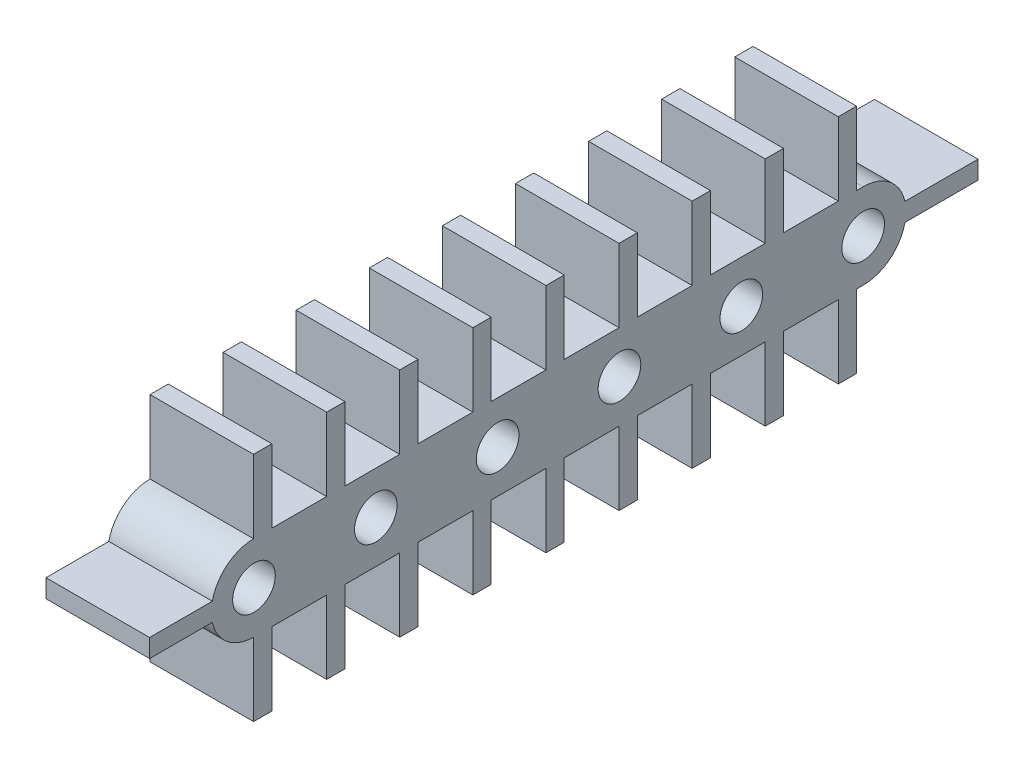
SolidWorks part; units mm, degrees
ref_plane "Front Plane" through (0, 0, 0) normal (0, 0, 1) x (1, 0, 0)
ref_plane "Top Plane" through (0, 0, 0) normal (0, 1, 0) x (1, 0, 0)
ref_plane "Right Plane" through (0, 0, 0) normal (1, 0, 0) x (0, 0, -1)
sketch "Sketch1" plane through (0, 0, 0) normal (1, 0, 0) x (0, 0, -1)
  line L0 (-265.082, 35) -> (-265.082, 95) construction
  line L1 (-250.082, 35) -> (-205.082, 35)
  line L3 (-250.082, -35) -> (-205.082, -35)
  line L5 (-185.082, 35) -> (-145.082, 35)
  line L7 (-265.082, 95) -> (-250.082, 95) construction
  line L8 (-250.082, 95) -> (-250.082, 35) construction
  line L9 (-265.082, 35) -> (-265.082, 95)
  line L10 (-265.082, 95) -> (-250.082, 95)
  line L11 (-250.082, 95) -> (-250.082, 35)
  line L23 (-264.7097, 0) -> (-265.3749, -51.003) construction
  line L27 (-205.082, 35) -> (-205.082, 95)
  line L28 (-205.082, 95) -> (-190.082, 95)
  line L29 (-190.082, 95) -> (-190.082, 35)
  line L30 (-205.082, 35) -> (-205.082, 95) construction
  line L31 (-205.082, 95) -> (-190.082, 95) construction
  line L32 (-190.082, 95) -> (-190.082, 35) construction
  line L33 (-145.082, 35) -> (-145.082, 95)
  line L34 (-145.082, 95) -> (-130.082, 95)
  line L35 (-130.082, 95) -> (-130.082, 35)
  line L36 (-145.082, 35) -> (-145.082, 95) construction
  line L37 (-145.082, 95) -> (-130.082, 95) construction
  line L38 (-130.082, 95) -> (-130.082, 35) construction
  line L39 (-85.082, 35) -> (-85.082, 95)
  line L40 (-85.082, 95) -> (-70.082, 95)
  line L41 (-70.082, 95) -> (-70.082, 35)
  line L42 (-85.082, 35) -> (-85.082, 95) construction
  line L43 (-85.082, 95) -> (-70.082, 95) construction
  line L44 (-70.082, 95) -> (-70.082, 35) construction
  line L45 (-25.082, 35) -> (-25.082, 95)
  line L46 (-25.082, 95) -> (-10.082, 95)
  line L47 (-10.082, 95) -> (-10.082, 35)
  line L48 (-25.082, 35) -> (-25.082, 95) construction
  line L49 (-25.082, 95) -> (-10.082, 95) construction
  line L50 (-10.082, 95) -> (-10.082, 35) construction
  line L51 (34.918, 35) -> (34.918, 95)
  line L52 (34.918, 95) -> (49.918, 95)
  line L53 (49.918, 95) -> (49.918, 35)
  line L54 (34.918, 35) -> (34.918, 95) construction
  line L55 (34.918, 95) -> (49.918, 95) construction
  line L56 (49.918, 95) -> (49.918, 35) construction
  line L57 (94.918, 35) -> (94.918, 95)
  line L58 (94.918, 95) -> (109.918, 95)
  line L59 (109.918, 95) -> (109.918, 35)
  line L60 (94.918, 35) -> (94.918, 95) construction
  line L61 (94.918, 95) -> (109.918, 95) construction
  line L62 (109.918, 95) -> (109.918, 35) construction
  line L63 (154.918, 35) -> (154.918, 95)
  line L64 (154.918, 95) -> (169.918, 95)
  line L65 (169.918, 95) -> (169.918, 35)
  line L66 (154.918, 35) -> (154.918, 95) construction
  line L67 (154.918, 95) -> (169.918, 95) construction
  line L68 (169.918, 95) -> (169.918, 35) construction
  line L69 (214.918, 35) -> (214.918, 95)
  line L70 (214.918, 95) -> (229.918, 95)
  line L71 (229.918, 95) -> (229.918, 35)
  line L72 (214.918, 35) -> (214.918, 95) construction
  line L73 (214.918, 95) -> (229.918, 95) construction
  line L74 (229.918, 95) -> (229.918, 35) construction
  line L75 (-190.082, 35) -> (-185.082, 35)
  line L76 (-130.082, 35) -> (-85.082, 35)
  line L77 (-70.082, 35) -> (-25.082, 35)
  line L78 (-10.082, 35) -> (34.918, 35)
  line L79 (49.918, 35) -> (94.918, 35)
  line L80 (109.918, 35) -> (154.918, 35)
  line L81 (169.918, 35) -> (214.918, 35)
  line L82 (229.918, 35) -> (235.3745, 35)
  line L83 (-264.7097, 0) -> (235.3745, 0) construction
  line L84 (229.918, -95) -> (229.918, -35) construction
  line L85 (214.918, -95) -> (229.918, -95) construction
  line L86 (214.918, -35) -> (214.918, -95) construction
  line L87 (169.918, -95) -> (169.918, -35) construction
  line L88 (154.918, -95) -> (169.918, -95) construction
  line L89 (154.918, -35) -> (154.918, -95) construction
  line L90 (109.918, -95) -> (109.918, -35) construction
  line L91 (94.918, -95) -> (109.918, -95) construction
  line L92 (94.918, -35) -> (94.918, -95) construction
  line L93 (49.918, -95) -> (49.918, -35) construction
  line L94 (34.918, -95) -> (49.918, -95) construction
  line L95 (34.918, -35) -> (34.918, -95) construction
  line L96 (-10.082, -95) -> (-10.082, -35) construction
  line L97 (-25.082, -95) -> (-10.082, -95) construction
  line L98 (-25.082, -35) -> (-25.082, -95) construction
  line L99 (-70.082, -95) -> (-70.082, -35) construction
  line L100 (-85.082, -95) -> (-70.082, -95) construction
  line L101 (-85.082, -35) -> (-85.082, -95) construction
  line L102 (-130.082, -95) -> (-130.082, -35) construction
  line L103 (-145.082, -95) -> (-130.082, -95) construction
  line L104 (-145.082, -35) -> (-145.082, -95) construction
  line L105 (-190.082, -95) -> (-190.082, -35) construction
  line L106 (-205.082, -95) -> (-190.082, -95) construction
  line L107 (-205.082, -35) -> (-205.082, -95) construction
  line L108 (-250.082, -95) -> (-250.082, -35) construction
  line L109 (-265.082, -95) -> (-250.082, -95) construction
  line L110 (-265.082, -35) -> (-265.082, -95) construction
  line L111 (229.918, -95) -> (229.918, -35)
  line L112 (214.918, -95) -> (229.918, -95)
  line L113 (214.918, -35) -> (214.918, -95)
  line L114 (169.918, -95) -> (169.918, -35)
  line L115 (154.918, -95) -> (169.918, -95)
  line L116 (154.918, -35) -> (154.918, -95)
  line L117 (109.918, -95) -> (109.918, -35)
  line L118 (94.918, -95) -> (109.918, -95)
  line L119 (94.918, -35) -> (94.918, -95)
  line L120 (49.918, -95) -> (49.918, -35)
  line L121 (34.918, -95) -> (49.918, -95)
  line L122 (34.918, -35) -> (34.918, -95)
  line L123 (-10.082, -95) -> (-10.082, -35)
  line L124 (-25.082, -95) -> (-10.082, -95)
  line L125 (-25.082, -35) -> (-25.082, -95)
  line L126 (-70.082, -95) -> (-70.082, -35)
  line L127 (-85.082, -95) -> (-70.082, -95)
  line L128 (-85.082, -35) -> (-85.082, -95)
  line L129 (-130.082, -95) -> (-130.082, -35)
  line L130 (-145.082, -95) -> (-130.082, -95)
  line L131 (-145.082, -35) -> (-145.082, -95)
  line L132 (-190.082, -95) -> (-190.082, -35)
  line L133 (-205.082, -95) -> (-190.082, -95)
  line L134 (-205.082, -35) -> (-205.082, -95)
  line L135 (-250.082, -95) -> (-250.082, -35)
  line L136 (-265.082, -95) -> (-250.082, -95)
  line L137 (-265.082, -35) -> (-265.082, -95)
  line L138 (-190.082, -35) -> (-145.082, -35)
  line L139 (-130.082, -35) -> (-85.082, -35)
  line L140 (-70.082, -35) -> (-25.082, -35)
  line L141 (-10.082, -35) -> (34.918, -35)
  line L142 (49.918, -35) -> (94.918, -35)
  line L143 (109.918, -35) -> (154.918, -35)
  line L144 (169.918, -35) -> (214.918, -35)
  line L145 (229.918, -35) -> (235.3745, -35)
  line L146 (0, 0) -> (0, 35) construction
  line L147 (0, 35) -> (0, -35) construction
  line L148 (-264.7097, 0) -> (-299.6285, 0) construction
  line L149 (-299.6285, 0) -> (-350.4285, 0) construction
  line L150 (-350.4285, 0) -> (-350.4285, 7.5) construction
  line L151 (-350.4285, 0) -> (-350.4285, -7.5) construction
  line L152 (-350.4285, 7.5) -> (-350.4285, -7.5)
  line L153 (-350.4285, 7.5) -> (-298.8987, 7.5)
  line L154 (-350.4285, -7.5) -> (-298.8987, -7.5)
  line L157 (329.5615, 0) -> (329.5615, 7.5) construction
  line L158 (329.5615, 0) -> (329.5615, -7.5) construction
  line L159 (329.5615, 7.5) -> (269.5615, 7.5)
  line L160 (329.5615, -7.5) -> (269.5615, -7.5)
  line L161 (329.5615, 7.5) -> (329.5615, -7.5)
  arc A0 (-265.082, 35) -> (-298.8987, 7.5) centre (-264.7097, 0) ccw
  arc A1 (235.3745, -35) -> (269.5615, -7.5) centre (235.3745, 0) ccw
  circle A2 centre (-264.7097, 0) radius 17.5
  circle A3 centre (-164.7097, 0) radius 17.5
  circle A4 centre (-64.7097, 0) radius 17.5
  circle A5 centre (35.2903, 0) radius 17.5
  circle A6 centre (135.2903, 0) radius 17.5
  circle A7 centre (235.2903, 0) radius 17.5
  arc A8 (-298.8987, -7.5) -> (-265.082, -35) centre (-264.7097, 0) ccw
  arc A9 (269.5615, 7.5) -> (235.3745, 35) centre (235.3745, 0) ccw
  point P0 (0, 0)
  dimension "D5" = 35
  dimension "D1" = 70
  dimension "D2" = 60
  dimension "D3" = 15
  dimension "D4" = 6
  dimension "D6" = 51.5298
  dimension "D7" = 7.5
  dimension "D8" = 60
  dimension "D9" = 7.5
extrude "Boss-Extrude1" add sketch "Sketch1" along normal blind 85
